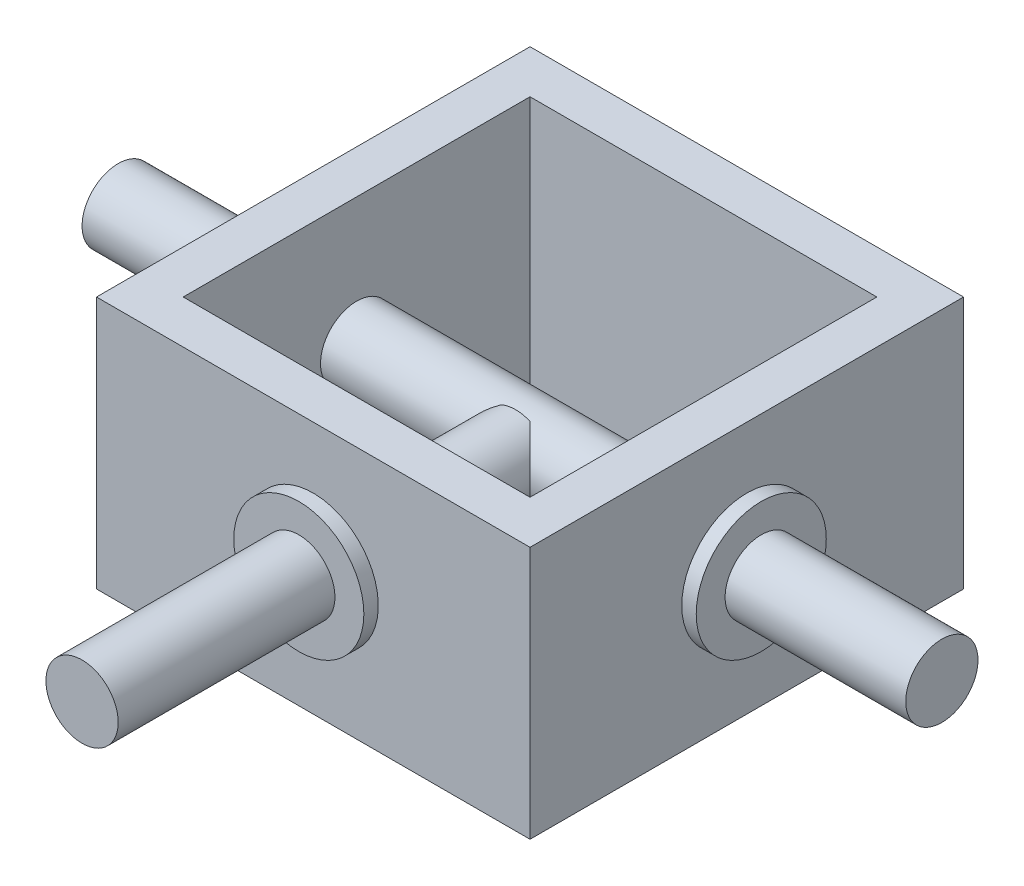
SolidWorks part; units mm, degrees
ref_plane "Front Plane" through (0, 0, 0) normal (0, 0, 1) x (1, 0, 0)
ref_plane "Top Plane" through (0, 0, 0) normal (0, 1, 0) x (1, 0, 0)
ref_plane "Right Plane" through (0, 0, 0) normal (1, 0, 0) x (0, 0, -1)
sketch "Sketch2" plane through (0, 0, 0) normal (0, 1, 0) x (1, 0, 0)
  line L1 (-30, -30) -> (30, -30)
  line L2 (-30, -30) -> (-30, 30)
  line L3 (-30, 30) -> (30, 30)
  line L4 (30, -30) -> (30, 30)
  line L5 (-30, -30) -> (30, 30) construction
  line L6 (-30, 30) -> (30, -30) construction
  line L7 (-24, -24) -> (24, -24)
  line L8 (-24, -24) -> (-24, 24)
  line L9 (-24, 24) -> (24, 24)
  line L10 (24, -24) -> (24, 24)
  line L11 (-24, -24) -> (24, 24) construction
  line L12 (-24, 24) -> (24, -24) construction
  point P0 (0, 0)
  point P6 (0, 0)
  dimension "D1" = 60
  dimension "D2" = 60
  dimension "D3" = 6
  dimension "D4" = 6
extrude "Boss-Extrude1" add sketch "Sketch2" along normal blind 35
sketch "Sketch3" plane through (30, 0, 0) normal (1, 0, 0) x (0, 0, -1)
  line L0 (-30, 35) -> (30, 0) construction
  circle A0 centre (0, 17.5) radius 5
  dimension "D1" = 10
extrude "Cut-Extrude1" cut sketch "Sketch3" against normal through all
sketch "Sketch4" plane through (0, 0, 30) normal (0, 0, 1) x (1, 0, 0)
  line L0 (-30, 35) -> (30, 0) construction
  circle A0 centre (0, 17.5) radius 5
  dimension "D1" = 10
extrude "Cut-Extrude2" cut sketch "Sketch4" against normal up to next
sketch "Sketch5" plane through (0, 0, 30) normal (0, 0, 1) x (1, 0, 0)
  circle A0 centre (0, 17.5) radius 9
  circle A1 centre (0, 17.5) radius 5
  dimension "D1" = 18
extrude "Boss-Extrude2" add sketch "Sketch5" along normal blind 2
sketch "Sketch7" plane through (30, 0, 0) normal (1, 0, 0) x (0, 0, -1)
  circle A0 centre (0, 17.5) radius 9
  circle A1 centre (0, 17.5) radius 5
  dimension "D1" = 18
extrude "Boss-Extrude3" add sketch "Sketch7" along normal blind 2
mirror "Mirror1" about plane through (0, 0, 0) normal (1, 0, 0) of "Boss-Extrude3"
sketch "Sketch8" plane through (0, 0, 0) normal (1, 0, 0) x (0, 0, -1)
  circle A0 centre (0, 17.5) radius 5
extrude "Boss-Extrude4" add sketch "Sketch8" along normal blind 57 and the other way blind 57
sketch "Sketch9" plane through (0, 0, 32) normal (0, 0, 1) x (1, 0, 0)
  circle A0 centre (0, 17.5) radius 5
extrude "Boss-Extrude5" add sketch "Sketch9" along normal blind 30 and the other way blind 30
